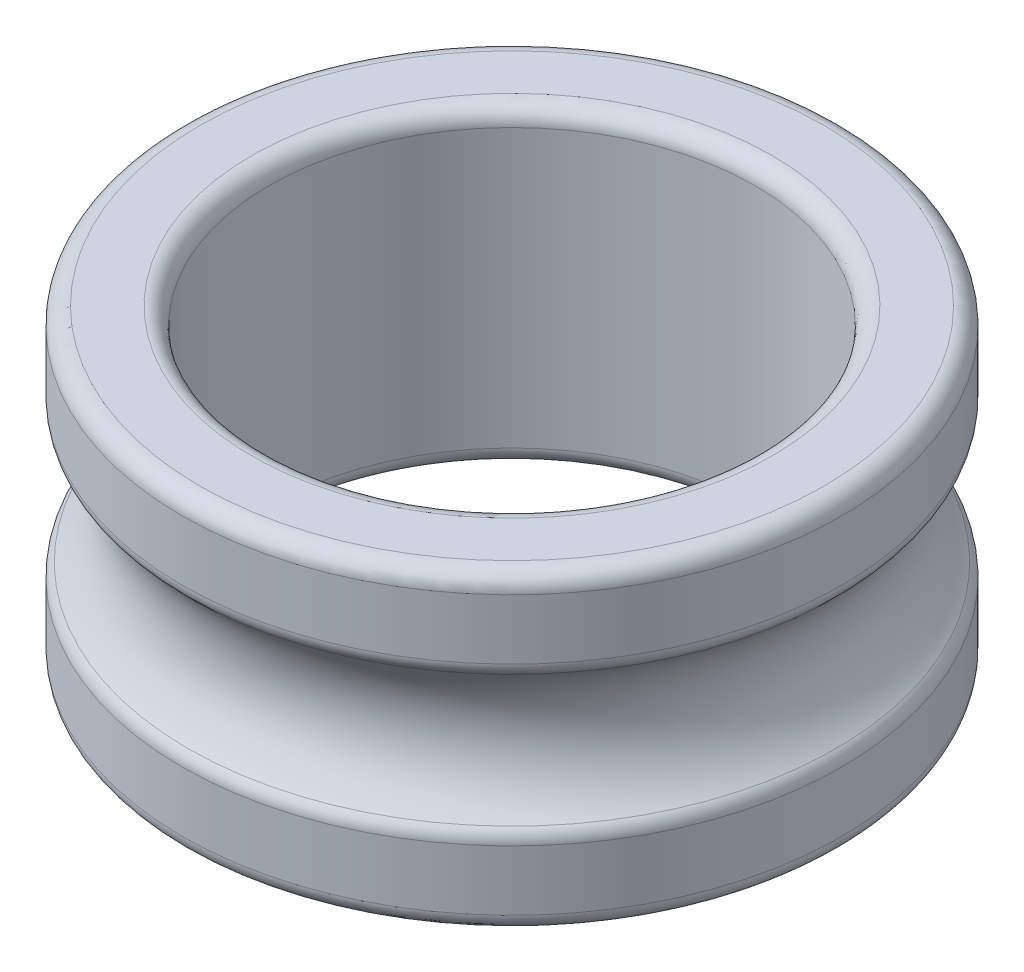
SolidWorks part; units mm, degrees
ref_plane "Front Plane" through (0, 0, 0) normal (0, 0, 1) x (1, 0, 0)
ref_plane "Top Plane" through (0, 0, 0) normal (0, 1, 0) x (1, 0, 0)
ref_plane "Right Plane" through (0, 0, 0) normal (1, 0, 0) x (0, 0, -1)
sketch "Sketch1" plane through (0, 0, 0) normal (1, 0, 0) x (0, 0, -1)
  line L0 (0, -9.8108) -> (0, 10.4568) construction
  line L1 (14, 8) -> (14, -8)
  line L2 (15, -9) -> (18, -9)
  line L3 (19, -8) -> (19, -4.539)
  line L4 (18, 9) -> (15, 9)
  line L5 (14, 0) -> (28.9693, 0) construction
  line L6 (19, 4.539) -> (19, 8)
  arc A0 (18.6612, 3.7888) -> (18.6612, -3.7888) centre (22, 0) ccw
  arc A1 (18.6612, -3.7888) -> (19, -4.539) centre (18, -4.539) cw
  arc A2 (18.6612, 3.7888) -> (19, 4.539) centre (18, 4.539) ccw
  arc A3 (18, -9) -> (19, -8) centre (18, -8) ccw
  arc A4 (14, -8) -> (15, -9) centre (15, -8) ccw
  arc A5 (19, 8) -> (18, 9) centre (18, 8) ccw
  arc A6 (14, 8) -> (15, 9) centre (15, 8) cw
  point P5 (14, 0)
  point P17 (19, 4.0623)
  dimension "D4" = 10.1
  dimension "D6" = 1
  dimension "D1" = 5
  dimension "D2" = 18
  dimension "D3" = 19
  dimension "D5" = 22
revolve "Revolve1" add sketch "Sketch1" angle 360 about L0
